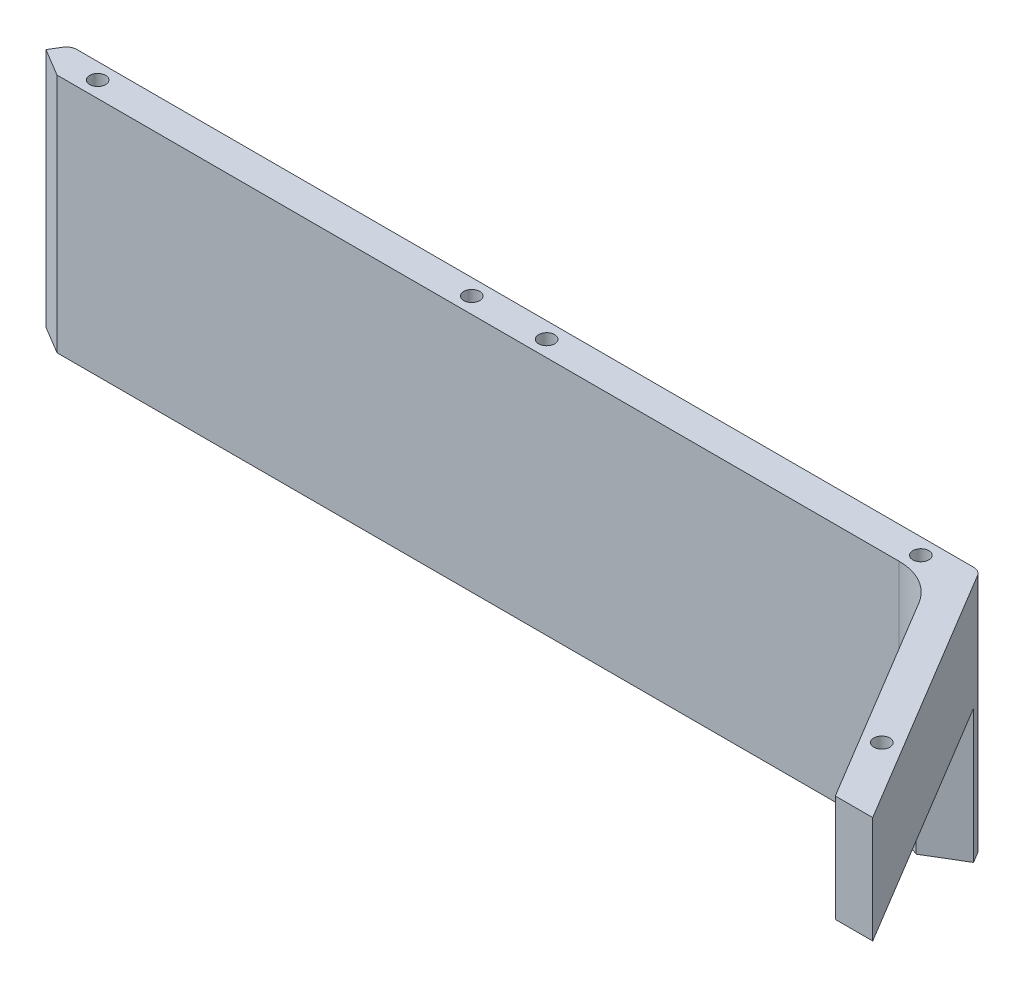
SolidWorks part; units mm, degrees
ref_plane "Front Plane" through (0, 0, 0) normal (0, 0, 1) x (1, 0, 0)
ref_plane "Top Plane" through (0, 0, 0) normal (0, 1, 0) x (1, 0, 0)
ref_plane "Right Plane" through (0, 0, 0) normal (1, 0, 0) x (0, 0, -1)
sketch "Sketch1" plane through (0, 0, 0) normal (0, 1, 0) x (1, 0, 0)
  line L0 (-115, 0) -> (-85, 50)
  line L1 (-85, 50) -> (85, 50)
  line L3 (81.6, 44) -> (-81.6, 44)
  line L4 (-81.6, 44) -> (-108, 0)
  line L5 (-108, 0) -> (-115, 0)
  line L6 (0, -55) -> (0, 55) construction
  line L7 (108, 0) -> (115, 0)
  line L8 (81.6, 44) -> (108, 0)
  line L9 (115, 0) -> (85, 50)
  dimension "D1" = 6
  dimension "D2" = 7
  dimension "D3" = 50
  dimension "D4" = 30
  dimension "D5" = 170
extrude "Boss-Extrude1" add sketch "Sketch1" along normal mid plane 45
sketch "Sketch2" plane through (0, 22.5, 0) normal (0, 1, 0) x (1, 0, 0)
  line L1 (-85, 50) -> (-115, 0) construction
  line L2 (85, 50) -> (-85, 50) construction
  line L3 (0, -55) -> (0, 55) construction
  circle A0 centre (-103.7014, 13) radius 1.5
  circle A1 centre (-77, 47) radius 1.5
  circle A2 centre (-7, 47) radius 1.5
  circle A3 centre (7, 47) radius 1.5
  circle A4 centre (77, 47) radius 1.5
  circle A5 centre (103.7014, 13) radius 1.5
  dimension "D2" = 3
  dimension "D3" = 3
  dimension "D5" = 3
  dimension "D1" = 70
  dimension "D4" = 7
  dimension "D6" = 3
  dimension "D7" = 3
  dimension "D8" = 3
  dimension "D9" = 37
extrude "Cut-Extrude1" cut sketch "Sketch2" against normal blind 5
fillet "Fillet1" radius 2 2 edges at (85, 0, -50) (-85, 0, -50)
sketch "Sketch4" plane through (84.5588, 0, -50.7353) normal (0.8575, 0, -0.5145) x (-0.5145, 0, -0.8575)
  line L0 (-59.167, 22.5) -> (-59.167, -22.5) construction
  line L1 (-59.167, 2.5) -> (-4.167, 2.5)
  line L2 (-59.167, 2.5) -> (-59.167, -22.5)
  line L3 (-59.167, -22.5) -> (-4.167, -22.5)
  line L4 (-4.167, 2.5) -> (-4.167, -22.5)
  line L5 (-59.167, 22.5) -> (-1.9899, 22.5) construction
  dimension "D1" = 55
  dimension "D2" = 25
  dimension "D3" = 20
extrude "Cut-Extrude3" cut sketch "Sketch4" against normal blind 10
sketch "Sketch5" plane through (-79.4118, 0, -47.6471) normal (0.8575, 0, 0.5145) x (0.5145, 0, -0.8575)
  line L0 (-59.167, 22.5) -> (-59.167, -22.5) construction
  line L1 (-59.167, -17.5) -> (-54.167, -17.5)
  line L2 (-59.167, -17.5) -> (-59.167, -22.5)
  line L3 (-59.167, -22.5) -> (-54.167, -22.5)
  line L4 (-54.167, -17.5) -> (-54.167, -22.5)
  line L5 (-55.5655, -22.5) -> (-4.2532, -22.5) construction
  dimension "D1" = 5
  dimension "D2" = 5
extrude "Cut-Extrude4" cut sketch "Sketch5" against normal blind 10
sketch "Sketch6" plane through (-79.4118, 0, -47.6471) normal (0.8575, 0, 0.5145) x (0.5145, 0, -0.8575)
  line L0 (-55.5655, 22.5) -> (-4.2532, 22.5) construction
  line L1 (-4.2532, -22.5) -> (-64.2532, -22.5)
  line L2 (-4.2532, -22.5) -> (-4.2532, 22.5)
  line L3 (-4.2532, 22.5) -> (-64.2532, 22.5)
  line L4 (-64.2532, -22.5) -> (-64.2532, 22.5)
  point P9 (-56.5945, 13.4331)
  point P10 (-56.5945, 13.4331)
  point P11 (-56.5945, 13.4331)
  point P12 (-56.5945, 13.4331)
  dimension "D1" = 0
  dimension "D2" = 60
extrude "Cut-Extrude5" cut sketch "Sketch6" against normal blind 10
fillet "Fillet2" radius 10 1 edges at (81.6, 12.5, -44)
